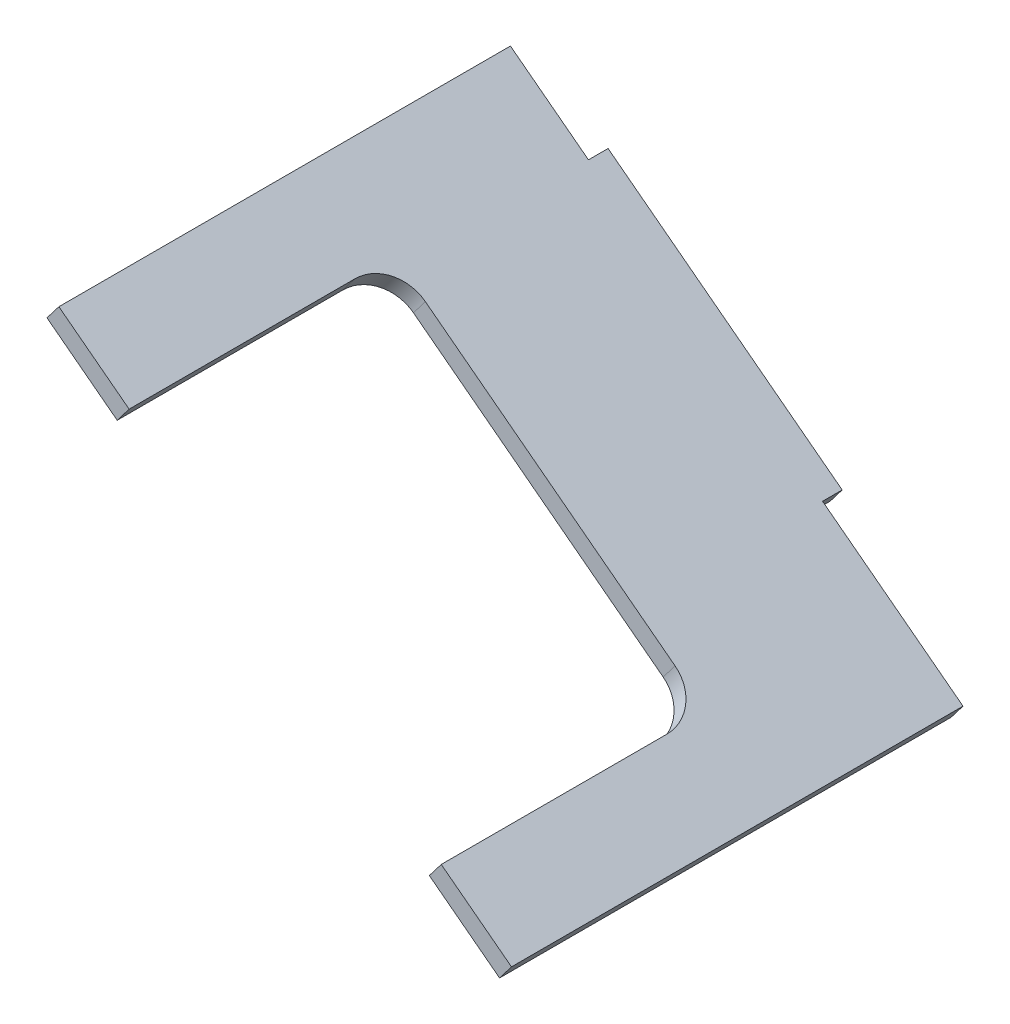
SolidWorks part; units mm, degrees
material "PVC rigido"
ref_plane "Piano frontale" through (0, 0, 0) normal (0, 0, 1) x (1, 0, 0)
ref_plane "Piano superiore" through (0, 0, 0) normal (0, 1, 0) x (1, 0, 0)
ref_plane "Piano destro" through (0, 0, 0) normal (1, 0, 0) x (0, 0, -1)
sketch "Schizzo1" plane through (0, 0, 0) normal (0, 0, 1) x (1, 0, 0)
  line L0 (62.3843, 50.5973) -> (38.5362, 68.798) construction
  line L1 (61.1709, 49.0074) -> (62.3843, 50.5973) construction
  line L2 (37.3228, 67.2081) -> (61.1709, 49.0074) construction
  line L3 (38.5362, 68.798) -> (37.3228, 67.2081) construction
  line L4 (62.3843, 50.5973) -> (38.5362, 68.798)
  line L5 (61.1709, 49.0074) -> (62.3843, 50.5973)
  line L6 (37.3228, 67.2081) -> (61.1709, 49.0074)
  line L7 (38.5362, 68.798) -> (37.3228, 67.2081)
extrude "Estrusione-Estrusione1" add sketch "Schizzo1" along normal up to surface (46 mm away) and the other way up to surface (2 mm away)
sketch "Schizzo2" plane through (46.1508, 60.4707, 0) normal (-0.6067, -0.7949, 0) x (0.7949, -0.6067, 0)
  line L0 (-11.1053, 0) -> (18.8947, 0) construction
  line L1 (-11.1053, 0) -> (-21.1053, 0)
  line L2 (-11.1053, 0) -> (-11.1053, 46)
  line L3 (-11.1053, 46) -> (-21.1053, 46)
  line L4 (-21.1053, 0) -> (-21.1053, 46)
  line L5 (-11.1053, 46) -> (-11.1053, -2) construction
  line L6 (18.8947, 46) -> (-11.1053, 46) construction
  line L7 (18.8947, 0) -> (36.8947, 0)
  line L8 (18.8947, 0) -> (18.8947, 46)
  line L9 (18.8947, 46) -> (36.8947, 46)
  line L10 (36.8947, 0) -> (36.8947, 46)
  line L11 (18.8947, 46) -> (18.8947, -2) construction
  dimension "D1" = 10
  dimension "D2" = 18
extrude "Estrusione-Estrusione2" add sketch "Schizzo2" against normal up to surface (2 mm away) up to face at (50.4602, 59.6977, 22)
sketch "Schizzo3" plane through (47.3642, 62.0605, 0) normal (0.6067, 0.7949, 0) x (0.7949, -0.6067, 0)
  line L0 (-21.1053, -46) -> (36.8947, -46) construction
  line L1 (-12.1053, -46) -> (27.8947, -46)
  line L2 (-12.1053, -46) -> (-12.1053, -19)
  line L3 (-12.1053, -19) -> (27.8947, -19)
  line L4 (27.8947, -46) -> (27.8947, -19)
  line L5 (-12.1053, -19) -> (-21.1053, -19) construction
  line L7 (-21.1053, 0) -> (-21.1053, -46) construction
  dimension "D1" = 27
  dimension "D2" = 40
  dimension "D3" = 9
extrude "Taglio-Estrusione1" cut sketch "Schizzo3" against normal blind 10
fillet "Raccordo1" radius 4 2 edges at (68.932, 44.3421, 19) (37.1345, 68.6098, 19)
